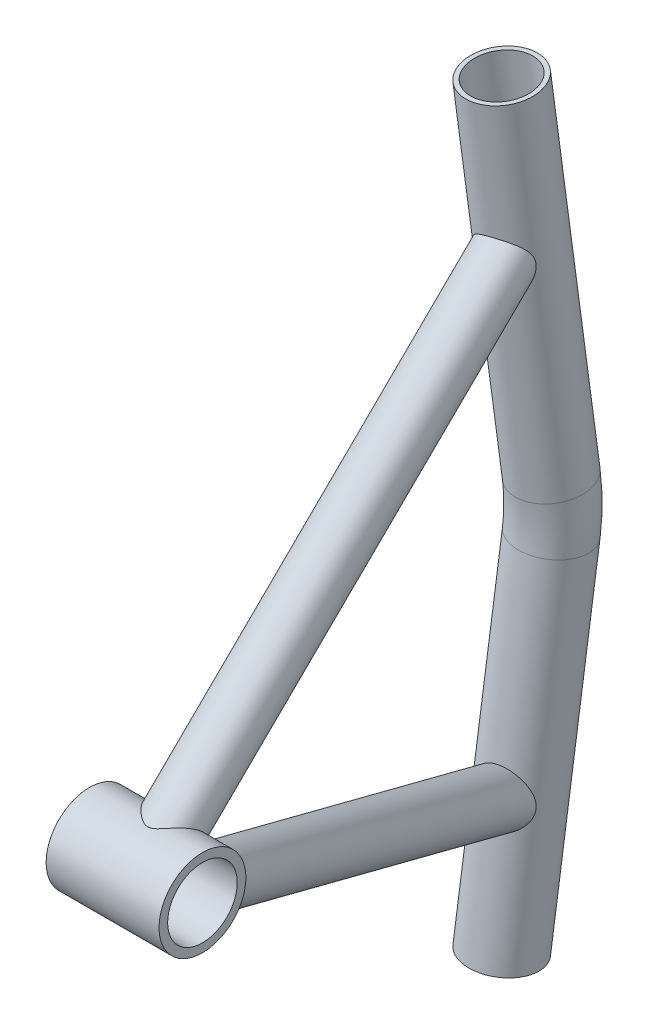
SolidWorks part; units mm, degrees
material "AISI 4130 Steel, normalized at 870C"
ref_plane "X-Y Datum" through (0, 0, 0) normal (0, 0, 1) x (1, 0, 0)
ref_plane "X-Z Datum" through (0, 0, 0) normal (0, 1, 0) x (1, 0, 0)
ref_plane "Y-Z Datum" through (0, 0, 0) normal (1, 0, 0) x (0, 0, -1)
ref_plane "FRH Reference" through (-89.8073, 0, -36.2845) normal (0.9272, 0, 0.3746) x (0.3746, 0, -0.9272)
sketch "Sketch6" plane through (0, 0, 0) normal (0, 1, 0) x (1, 0, 0)
  line L1 (20.6375, 15.875) -> (-20.6375, 15.875)
  line L2 (20.6375, 15.875) -> (20.6375, 12.7254)
  line L3 (20.6375, 12.7254) -> (-20.6375, 12.7254)
  line L4 (-20.6375, 15.875) -> (-20.6375, 12.7254)
  line L9 (-66.7868, 0) -> (90.4215, 0) construction
revolve "Revolve2" add sketch "Sketch6" angle 360 about L9
sketch3d "3DSketch2"
  line L0 (0, 0, 0) -> (0, 11.2253, -11.2253) construction
  line L1 (-66.7868, 0, 0) -> (90.4215, 0, 0) construction
  line L2 (0, 0, 0) -> (0, 0, 15.875) construction
  line L3 (0, 0, 0) -> (0, 0, -15.875) construction
  line L4 (0, 0, 0) -> (0, -11.2253, -11.2253) construction
  line L7 (20.6375, 0, -15.875) -> (-20.6375, 0, -15.875) construction
  line L8 (0, 11.2253, -11.2253) -> (-45.6789, 89.2363, -182.5965)
  line L9 (0, -11.2253, -11.2253) -> (-45.6789, -89.2363, -182.5965)
  line L10 (-47.9371, 138.4715, -177.9436) -> (-42.012, 9.2876, -190.1521)
  line L11 (-42.012, -9.2876, -190.1521) -> (-47.9371, -138.4715, -177.9436)
  line L12 (0, 0, 0) -> (86.995, 0, 0) construction
  arc A0 (-42.012, 9.2876, -190.1521) -> (-42.012, -9.2876, -190.1521) centre (-80.6149, 0, -110.6111) ccw
  point P20 (-160.5935, 0, -149.4264)
  dimension "D1" = 45
  dimension "D2" = 135
  dimension "D3" = 45
  dimension "D4" = 135
  dimension "D5" = 193.7534
  dimension "D7" = 47.485
  dimension "D6" = 155.523
  dimension "D8" = 86.995
ref_plane "Plane1" through (-45.6789, 89.2363, -182.5965) normal (-0.2358, 0.4026, -0.8845) x (-0.9718, -0.0977, 0.2146)
sketch "Sketch10" plane through (-45.6789, 89.2363, -182.5965) normal (-0.2358, 0.4026, -0.8845) x (-0.9718, -0.0977, 0.2146)
  circle A0 centre (0, 0) radius 9.525
  circle A1 centre (0, 0) radius 7.874
  dimension "D1" = 19.05
  dimension "D2" = 1.651
extrude "Boss-Extrude1" add sketch "Sketch10" against normal up to surface (203.9812 mm away) separate body
ref_plane "Plane2" through (-45.6789, -89.2363, -182.5965) normal (-0.2358, -0.4026, -0.8845) x (-0.9718, 0.0977, 0.2146)
sketch "Sketch11" plane through (-45.6789, -89.2363, -182.5965) normal (-0.2358, -0.4026, -0.8845) x (-0.9718, 0.0977, 0.2146)
  circle A0 centre (0, 0) radius 9.525
  circle A1 centre (0, 0) radius 7.874
  dimension "D1" = 19.05
  dimension "D2" = 1.651
extrude "Boss-Extrude2" add sketch "Sketch11" against normal up to surface (193.2326 mm away) separate body
ref_plane "Plane3" through (-47.9371, -138.4715, -177.9436) normal (-0.0456, -0.9945, 0.094) x (-0.999, 0.0454, -0.0043)
sketch "Sketch12" plane through (-47.9371, -138.4715, -177.9436) normal (-0.0456, -0.9945, 0.094) x (-0.999, 0.0454, -0.0043)
  circle A0 centre (0, 0) radius 12.7
  dimension "D1" = 25.4
sweep "Cut-Sweep1" cut profiles "Sketch12" path "3DSketch2"
ref_plane "Plane4" through (-108.6951, 0, -52.752) normal (0.8996, 0, 0.4366) x (0.4366, 0, -0.8996)
sketch "Sketch14" plane through (-108.6951, 0, -52.752) normal (0.8996, 0, 0.4366) x (0.4366, 0, -0.8996)
  line L0 (139.1563, 138.4715) -> (152.7267, 9.2876)
  line L1 (152.7267, -9.2876) -> (139.1563, -138.4715)
  arc A0 (152.7267, 9.2876) -> (152.7267, -9.2876) centre (64.3131, 0) cw
sketch "Sketch15" plane through (-47.9371, -138.4715, -177.9436) normal (-0.0456, -0.9945, 0.094) x (-0.999, 0.0454, -0.0043)
  circle A0 centre (0, 0) radius 12.7
  circle A1 centre (0, 0) radius 11.049
  dimension "D1" = 25.4
  dimension "D2" = 1.651
sweep "Sweep2" add profiles "Sketch15" path "Sketch14"
equation "\"Tube_Thickness\"=0.75"
equation "\"Wall_Thickness\"=0.065"
